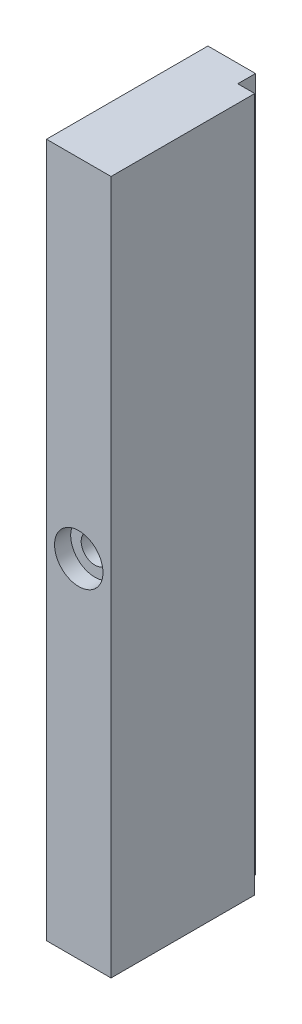
SolidWorks part; units mm, degrees
other "Ballast End Stop Front"
ref_plane "Front Plane" through (0, 0, 0) normal (0, 0, 1) x (1, 0, 0)
ref_plane "Top Plane" through (0, 0, 0) normal (0, 1, 0) x (1, 0, 0)
ref_plane "Right Plane" through (0, 0, 0) normal (1, 0, 0) x (0, 0, -1)
sketch3d "Main Profile Sketch datum points"
  point P0 (0, 0, 140)
  point P1 (10, 0, 140)
  point P2 (0, 10, 140)
ref_plane "Main Profile Sketch plane" through (0, 0, 140) normal (0, 0, 1) x (1, 0, 0)
sketch "Main Profile Sketch" plane through (0, 0, 140) normal (0, 0, 1) x (1, 0, 0)
  line L0 (132.5, 43) -> (140.5, 43)
  line L1 (140.5, 43) -> (140.5, -43)
  line L2 (132.5, -43) -> (140.5, -43)
  line L3 (132.5, 43) -> (132.5, -43)
  circle A0 centre (136.5, 0) radius 3
extrude "Main Extrusion" add sketch "Main Profile Sketch" against normal blind 2 separate body
sketch3d "Detail Profile 2 Sketch datum points"
  point P0 (0, 0, 138)
  point P1 (10, 0, 138)
  point P2 (0, 10, 138)
ref_plane "Detail Profile 2 Sketch plane" through (0, 0, 138) normal (0, 0, 1) x (1, 0, 0)
sketch "Detail Profile 2 Sketch" plane through (0, 0, 138) normal (0, 0, 1) x (1, 0, 0)
  line L0 (132.5, 43) -> (140.5, 43)
  line L1 (140.5, 43) -> (140.5, -43)
  line L2 (132.5, -43) -> (140.5, -43)
  line L3 (132.5, 43) -> (132.5, -43)
  circle A0 centre (136.5, 0) radius 1.7
extrude "Detail Extrusion 2" add sketch "Detail Profile 2 Sketch" against normal blind 15.8
sketch3d "Detail Profile 3 Sketch datum points"
  point P0 (0, 0, 122.2)
  point P1 (10, 0, 122.2)
  point P2 (0, 10, 122.2)
ref_plane "Detail Profile 3 Sketch plane" through (0, 0, 122.2) normal (0, 0, 1) x (1, 0, 0)
sketch "Detail Profile 3 Sketch" plane through (0, 0, 122.2) normal (0, 0, 1) x (1, 0, 0)
  line L0 (132.5, 43) -> (138.4, 43)
  line L1 (138.4, 43) -> (138.4, -43)
  line L2 (132.5, -43) -> (138.4, -43)
  line L3 (132.5, 43) -> (132.5, -43)
  circle A0 centre (136.5, 0) radius 1.7
extrude "Detail Extrusion 3" add sketch "Detail Profile 3 Sketch" against normal blind 2.2
